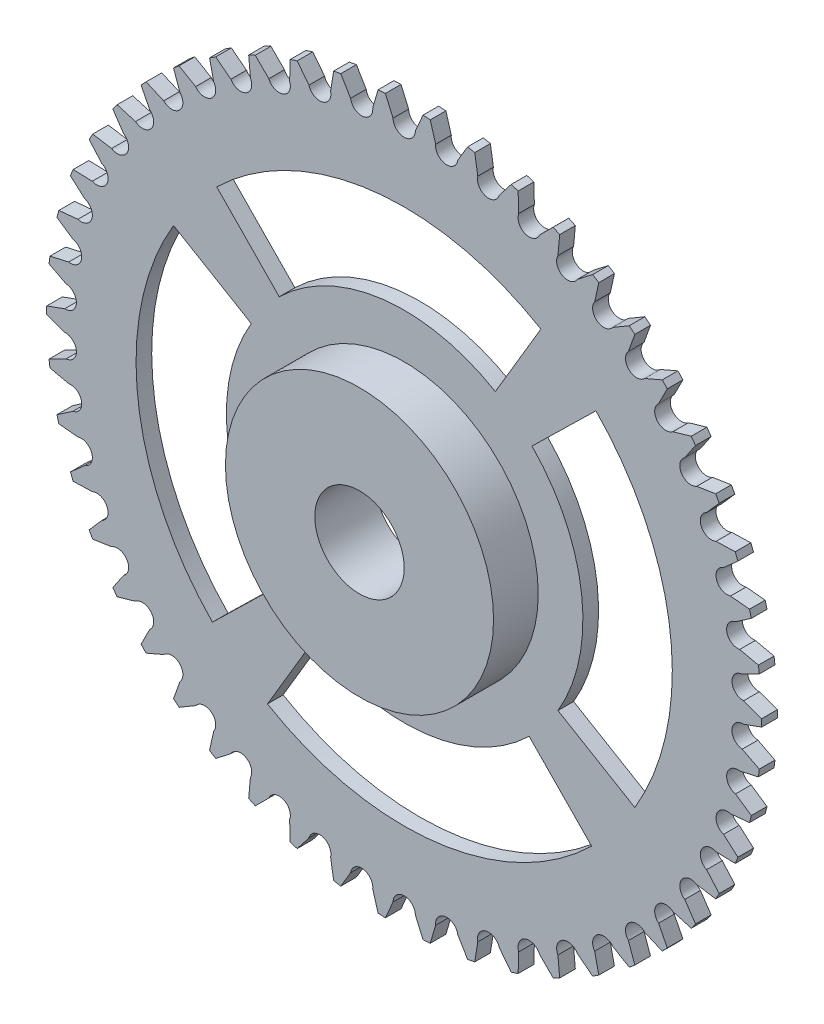
SolidWorks part; units mm, degrees
ref_plane "Front Plane" through (0, 0, 0) normal (0, 0, 1) x (1, 0, 0)
ref_plane "Top Plane" through (0, 0, 0) normal (0, 1, 0) x (1, 0, 0)
ref_plane "Right Plane" through (0, 0, 0) normal (1, 0, 0) x (0, 0, -1)
sketch "Sketch1" plane through (0, 0, 0) normal (0, 0, 1) x (1, 0, 0)
  circle A0 centre (0, 0) radius 80
  dimension "D1" = 160
extrude "Boss-Extrude1" add sketch "Sketch1" along normal blind 3.5
sketch "Sketch2" plane through (0, 0, 3.5) normal (0, 0, 1) x (1, 0, 0)
  circle A0 centre (0, 0) radius 10
  dimension "D1" = 20
extrude "Cut-Extrude1" cut sketch "Sketch2" against normal blind 3.5
sketch "Sketch3" plane through (0, 0, 3.5) normal (0, 0, 1) x (1, 0, 0)
  circle A0 centre (0, 0) radius 30
  circle A1 centre (0, 0) radius 10
  dimension "D1" = 20
extrude "Boss-Extrude2" add sketch "Sketch3" along normal blind 10
sketch "Sketch6" plane through (0, 0, 3.5) normal (0, 0, 1) x (1, 0, 0)
  line L0 (-42.9079, -41.9393) -> (-28.4525, -27.8105)
  line L1 (30.5912, 51.6157) -> (20.3941, 34.4105)
  line L2 (-41.9393, 42.9079) -> (-27.9596, 28.6053)
  line L10 (42.9079, 41.9393) -> (28.6053, 27.9596)
  line L11 (51.6157, -30.5912) -> (34.4105, -20.3941)
  line L12 (41.9393, -42.9079) -> (27.9596, -28.6053)
  line L13 (-30.5912, -51.6157) -> (-20.3941, -34.4105)
  line L15 (-34.2268, 20.2853) -> (-51.6157, 30.5912)
  arc A3 (-41.9393, 42.9079) -> (30.5912, 51.6157) centre (0, 0) cw
  arc A4 (-27.9596, 28.6053) -> (20.3941, 34.4105) centre (0, 0) cw
  arc A5 (28.6053, 27.9596) -> (34.4105, -20.3941) centre (0, 0) cw
  arc A6 (51.6157, -30.5912) -> (42.9079, 41.9393) centre (0, 0) ccw
  arc A7 (-30.5912, -51.6157) -> (41.9393, -42.9079) centre (0, 0) ccw
  arc A8 (-20.3941, -34.4105) -> (27.9596, -28.6053) centre (0, 0) ccw
  arc A9 (-51.6157, 30.5912) -> (-42.9079, -41.9393) centre (0, 0) ccw
  arc A10 (-34.2268, 20.2853) -> (-28.4525, -27.8105) centre (0, 0) ccw
extrude "Cut-Extrude2" cut sketch "Sketch6" against normal blind 10
sketch "Sketch8" plane through (0, 0, 3.5) normal (0, 0, 1) x (1, 0, 0)
  line L1 (-2.4997, 75.9589) -> (-4.2086, 79.8892)
  line L2 (2.4997, 75.9589) -> (4.2086, 79.8892)
  circle A1 centre (0, 0) radius 80 construction
  arc A3 (-2.4997, 75.9589) -> (2.4997, 75.9589) centre (0, 76) ccw
  arc A4 (-4.2086, 79.8892) -> (4.2086, 79.8892) centre (0, 47.0957) cw
extrude "Cut-Extrude4" cut sketch "Sketch8" against normal blind 10
pattern_circular "CirPattern2" count 50 over 360 about axis through (0, 0, 0) along (0, 0, 1) of "Cut-Extrude4"
